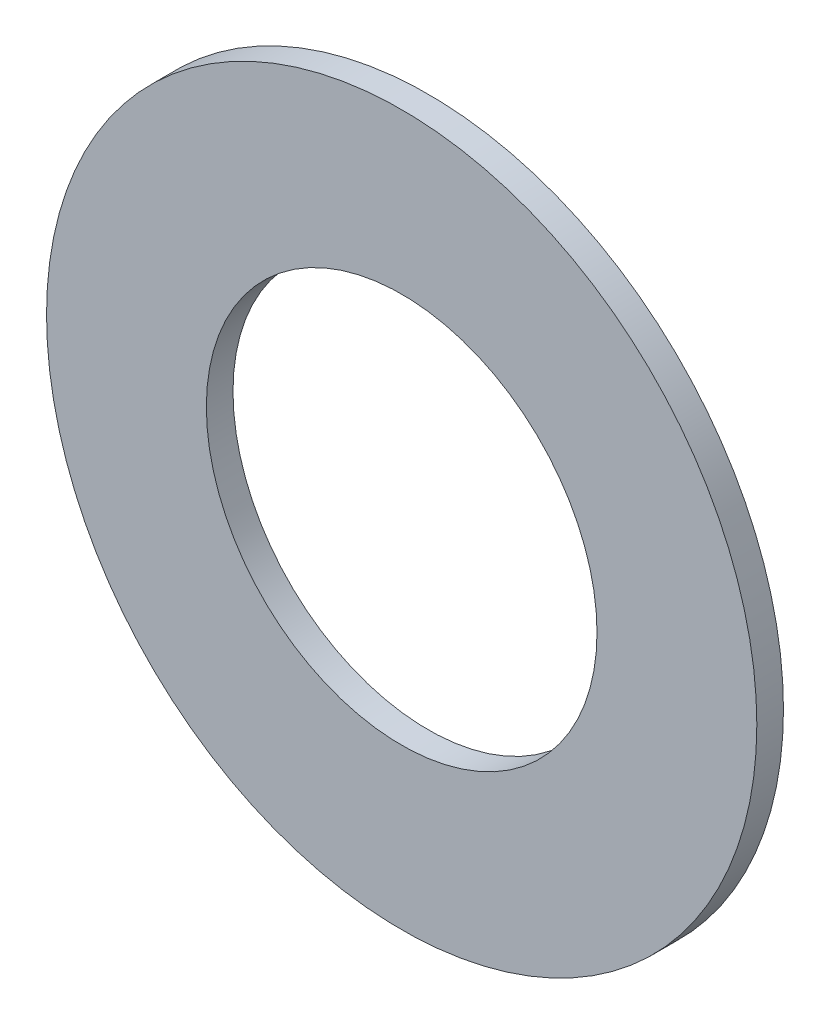
SolidWorks part; units mm, degrees
material "PA Type 6"
ref_plane "Front Plane" through (0, 0, 0) normal (0, 0, 1) x (1, 0, 0)
ref_plane "Top Plane" through (0, 0, 0) normal (0, 1, 0) x (1, 0, 0)
ref_plane "Right Plane" through (0, 0, 0) normal (1, 0, 0) x (0, 0, -1)
sketch "Sketch1" plane through (0, 0, 0) normal (0, 0, 1) x (1, 0, 0)
  circle A0 centre (0, 0) radius 10
  circle A1 centre (0, 0) radius 5.5
  dimension "D1" = 20
  dimension "D2" = 11
extrude "Boss-Extrude1" add sketch "Sketch1" along normal blind 0.75
